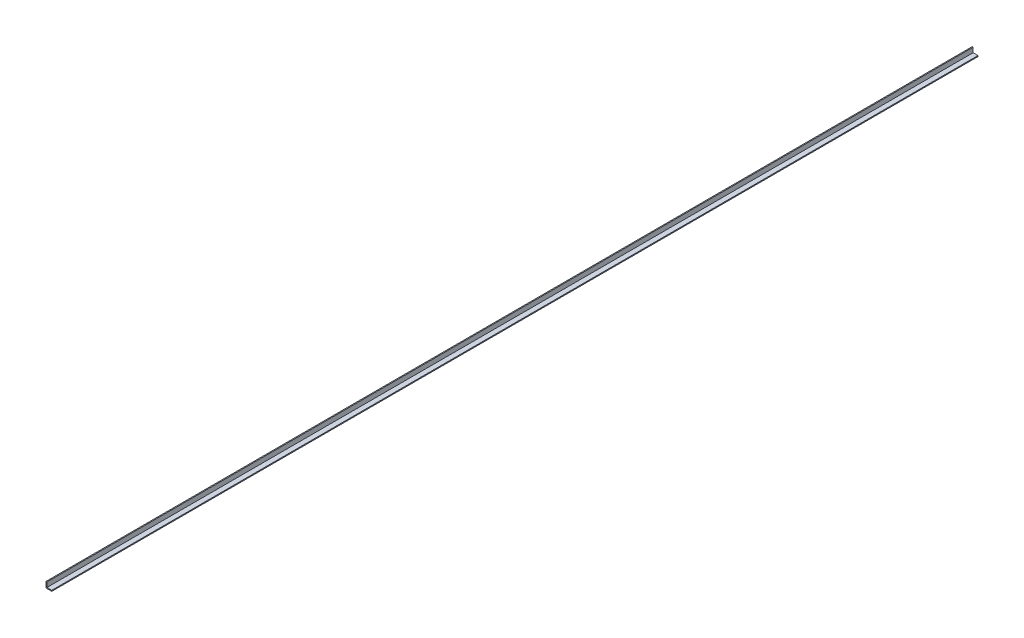
SolidWorks part; units mm, degrees
material "ASTM A36 Acero"
ref_plane "Alzado" through (0, 0, 0) normal (0, 0, 1) x (1, 0, 0)
ref_plane "Planta" through (0, 0, 0) normal (0, 1, 0) x (1, 0, 0)
ref_plane "Vista lateral" through (0, 0, 0) normal (1, 0, 0) x (0, 0, -1)
sketch "Croquis1" plane through (0, 0, 0) normal (0, 0, 1) x (1, 0, 0)
  line L0 (0, 38.1) -> (0, 0)
  line L1 (0, 0) -> (38.1, 0)
  line L2 (38.1, 0) -> (38.1, 6.35)
  line L3 (38.1, 6.35) -> (6.35, 6.35)
  line L4 (6.35, 6.35) -> (6.35, 38.1)
  line L5 (6.35, 38.1) -> (0, 38.1)
  dimension "D1" = 6.35
  dimension "D2" = 38.1
extrude "Saliente-Extruir1" add sketch "Croquis1" against normal blind 6100
